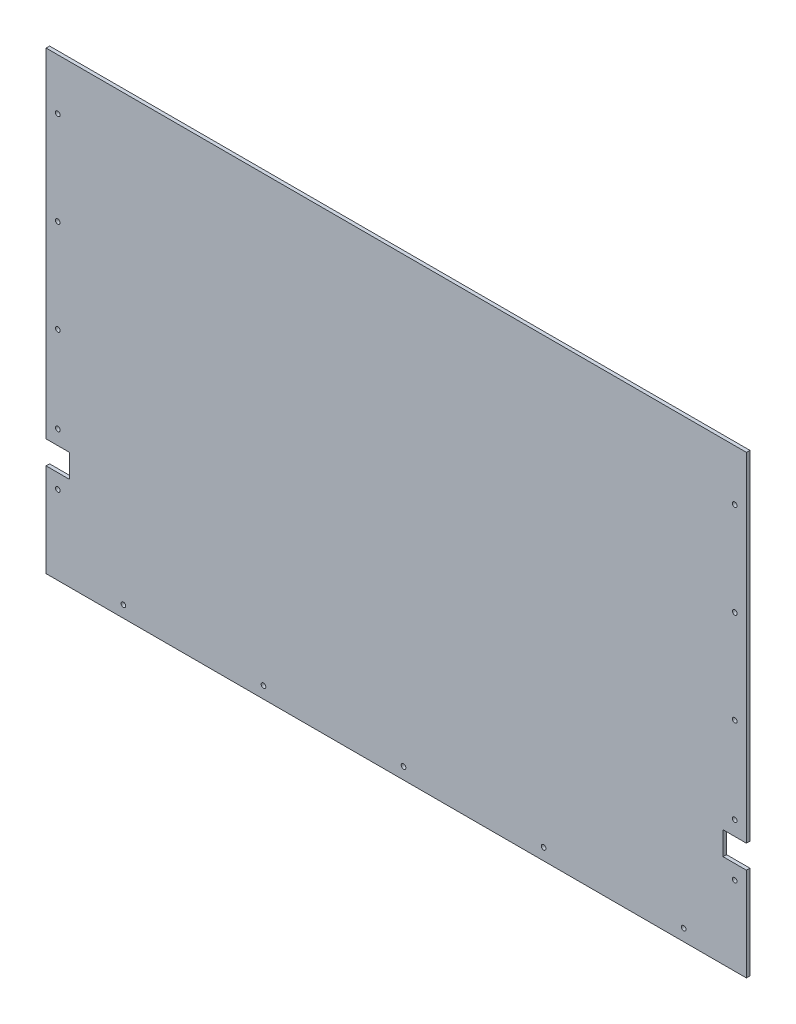
SolidWorks part; units mm, degrees
ref_plane "Płaszczyzna przednia" through (0, 0, 0) normal (0, 0, 1) x (1, 0, 0)
ref_plane "Płaszczyzna górna" through (0, 0, 0) normal (0, 1, 0) x (1, 0, 0)
ref_plane "Płaszczyzna prawa" through (0, 0, 0) normal (1, 0, 0) x (0, 0, -1)
sketch "Sketch1" plane through (0, 0, 0) normal (0, 0, 1) x (1, 0, 0)
  line L1 (0, 0) -> (600, 0)
  line L2 (0, 0) -> (0, 390)
  line L3 (0, 390) -> (600, 390)
  line L4 (600, 0) -> (600, 390)
  line L5 (0, 0) -> (600, 390) construction
  line L6 (0, 390) -> (600, 0) construction
  point P4 (300, 195)
  dimension "D1" = 600
  dimension "D2" = 390
extrude "Boss-Extrude1" add sketch "Sketch1" along normal blind 3
sketch "Sketch2" plane through (0, 0, 3) normal (0, 0, 1) x (1, 0, 0)
  line L0 (600, 0) -> (600, 390) construction
  line L1 (600, 100) -> (580, 100)
  line L2 (600, 100) -> (600, 80)
  line L3 (600, 80) -> (580, 80)
  line L4 (580, 100) -> (580, 80)
  line L5 (600, 100) -> (580, 80) construction
  line L6 (600, 80) -> (580, 100) construction
  line L7 (0, 390) -> (0, 0) construction
  line L8 (0, 100) -> (20, 100)
  line L9 (0, 100) -> (0, 80)
  line L10 (0, 80) -> (20, 80)
  line L11 (20, 100) -> (20, 80)
  line L12 (0, 100) -> (20, 80) construction
  line L13 (0, 80) -> (20, 100) construction
  line L14 (600, 390) -> (0, 390) construction
  point P4 (590, 90)
  point P11 (10, 90)
  dimension "D1" = 290
  dimension "D2" = 20
  dimension "D3" = 20
  dimension "D4" = 290
  dimension "D5" = 20
  dimension "D6" = 20
extrude "Cut-Extrude1" cut sketch "Sketch2" against normal blind 3
hole_wizard "Ø4.0mm Dowel Hole1" positions "Sketch3" profile "Sketch4" hole size "Ø4.0" standard "ANSI Metric" end condition through all
sketch "Sketch3" plane through (0, 0, 0) normal (0, 0, -1) x (-1, 0, 0)
  line L0 (-600, 100) -> (-600, 390) construction
  line L1 (-600, 390) -> (0, 390) construction
  point P0 (-590, 346.25)
  point P15 (-10, 346.25)
  point P16 (-10, 266.25)
  point P17 (-10, 186.25)
  point P18 (-590, 266.25)
  point P19 (-590, 186.25)
  point P20 (-590, 112.4496)
  point P23 (-590, 67.5504)
  point P26 (-10, 112.4496)
  point P29 (-10, 67.5504)
  point P32 (-66.25, 10.0691)
  point P35 (-186.25, 10.0691)
  point P38 (-306.25, 10.0691)
  point P41 (-426.25, 10.0691)
  point P44 (-546.25, 10.0691)
  dimension "D1" = 10
  dimension "D2" = 43.75
  dimension "D3" = 2
  dimension "D4" = 3
sketch "Sketch4" plane through (590, 346.25, 0) normal (1, 0, 0) x (0, 1, 0)
  line L0 (0, 0) -> (0, 3)
  line L1 (0, 3) -> (2, 3)
  line L2 (2, 3) -> (2, 0)
  line L5 (2, 0) -> (0, 0)
  line L11 (0, -6.35) -> (0, 107.95) construction
  dimension "Thru Hole Dia." = 4
  dimension "Thru Hole Depth" = 3
